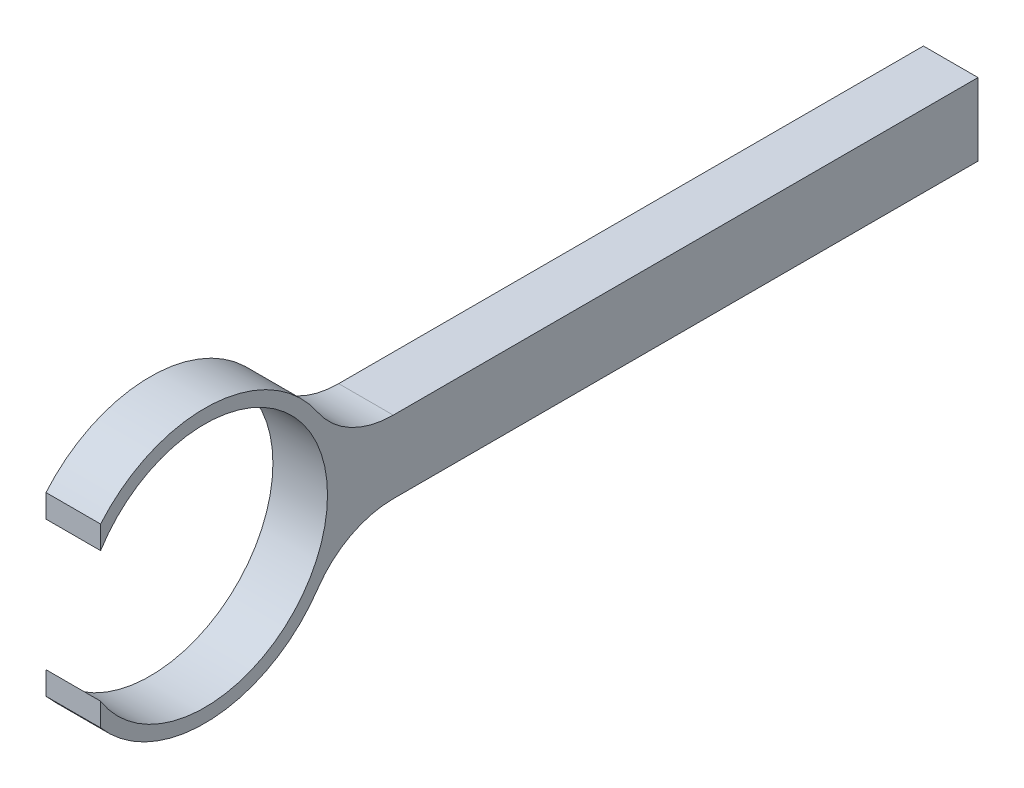
SolidWorks part; units mm, degrees
ref_plane "Front Plane" through (0, 0, 0) normal (0, 0, 1) x (1, 0, 0)
ref_plane "Top Plane" through (0, 0, 0) normal (0, 1, 0) x (1, 0, 0)
ref_plane "Right Plane" through (0, 0, 0) normal (1, 0, 0) x (0, 0, -1)
sketch "Sketch1" plane through (0, 0, 0) normal (1, 0, 0) x (0, 0, -1)
  line L0 (-11.4427, 23.6686) -> (-11.4427, -23.301)
  line L1 (0, 0) -> (109.6696, 0) construction
  line L2 (14.4623, -3.9801) -> (85, -3.9801)
  line L3 (85, -3.9801) -> (85, 3.9801)
  line L4 (14.4623, 3.9801) -> (85, 3.9801)
  line L9 (15, 32.3322) -> (15, -32.3322) construction
  circle A0 centre (0, 0) radius 15
  circle A1 centre (0, 0) radius 13.5
  point P8 (25.0172, 0)
  point P14 (85, 0)
  point P18 (15, 0)
  dimension "D1" = 27
  dimension "D2" = 1.5
  dimension "D4" = 70
extrude "Boss-Extrude1" add sketch "Sketch1" along normal blind 6
fillet "Fillet1" radius 10 2 edges at (3, 3.9801, -14.4623) (3, -3.9801, -14.4623)
